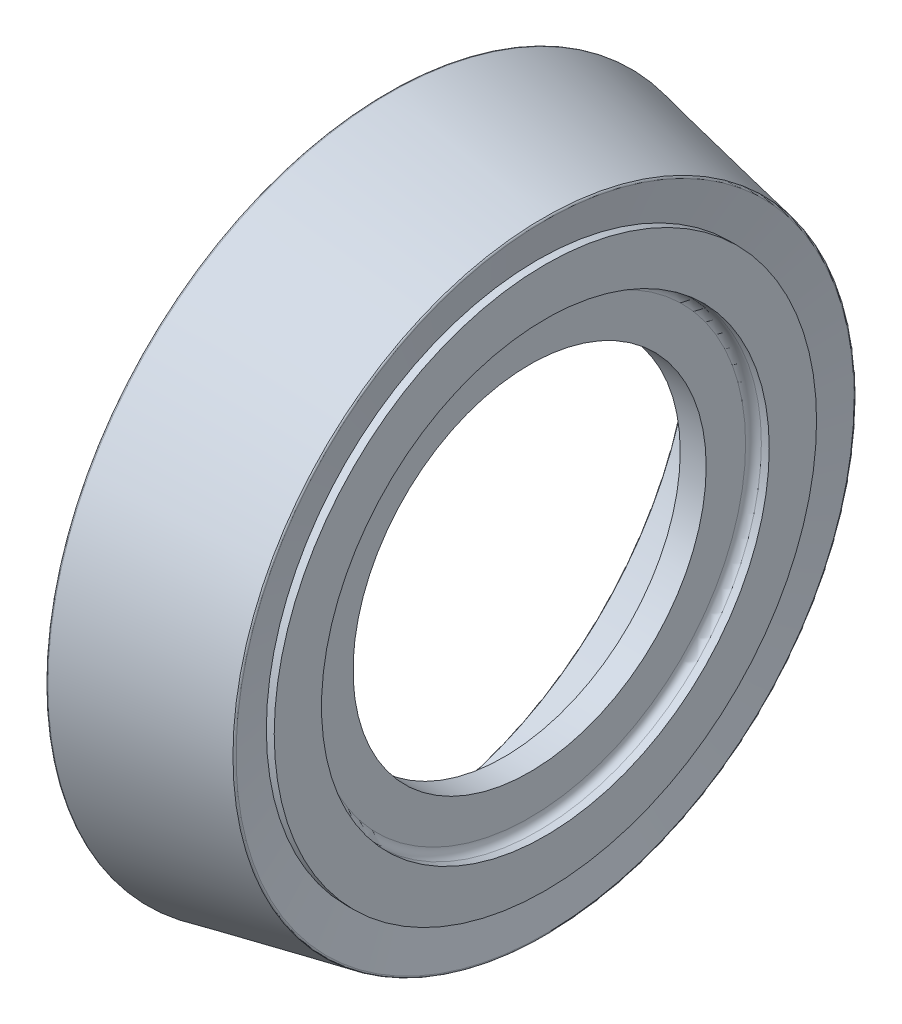
SolidWorks part; units mm, degrees
ref_plane "Płaszczyzna przednia" through (0, 0, 0) normal (0, 0, 1) x (1, 0, 0)
ref_plane "Płaszczyzna górna" through (0, 0, 0) normal (0, 1, 0) x (1, 0, 0)
ref_plane "Płaszczyzna prawa" through (0, 0, 0) normal (1, 0, 0) x (0, 0, -1)
sketch "Szkic1" plane through (0, 0, 0) normal (0, 0, 1) x (1, 0, 0)
  line L0 (1, 2.5) -> (1, 5.5)
  line L1 (1, 5.5) -> (0.5, 5.5)
  line L2 (0.5, 5.5) -> (0.9804, 7.9019)
  line L3 (1, 2.5) -> (0.5, 2.5)
  line L4 (0, 2) -> (0, -0.5)
  line L5 (-9, 7.582) -> (-9, 9.878)
  line L6 (0.9019, 8.0196) -> (-8.8804, 9.9761)
  line L7 (-8.9196, 7.4839) -> (-1.6456, 6.0291)
  line L8 (-1.6456, 6.0291) -> (-1.6456, -0.5)
  line L9 (-1.6456, -0.5) -> (0, -0.5)
  line L11 (0, -11.7) -> (-1.6456, -11.7)
  arc A0 (0, 2) -> (0.5, 2.5) centre (0.5, 2) cw
  arc A1 (0.9804, 7.9019) -> (0.9019, 8.0196) centre (0.8823, 7.9216) ccw
  arc A2 (-9, 7.582) -> (-8.9196, 7.4839) centre (-8.9, 7.582) ccw
  arc A3 (-8.8804, 9.9761) -> (-9, 9.878) centre (-8.9, 9.878) ccw
  point P12 (0, 2.5)
  point P15 (1, 8)
  point P18 (-9, 7.5)
  point P22 (-9, 10)
  dimension "D9" = 0.5
  dimension "D10" = 0.1
  dimension "D11" = 0.1
  dimension "D12" = 1.6456
  dimension "D1" = 3
  dimension "D2" = 1
  dimension "D3" = 3
  dimension "D4" = 0.5
  dimension "D5" = 2.5
  dimension "D6" = 10
  dimension "D7" = 2
  dimension "D8" = 7.5
  dimension "D13" = 2.5
  dimension "D14" = 3
  dimension "D15" = 1
  dimension "D16" = 11.2
  dimension "D17" = 1.6456
revolve "Obrót1" add sketch "Szkic1" angle 360 about L11
